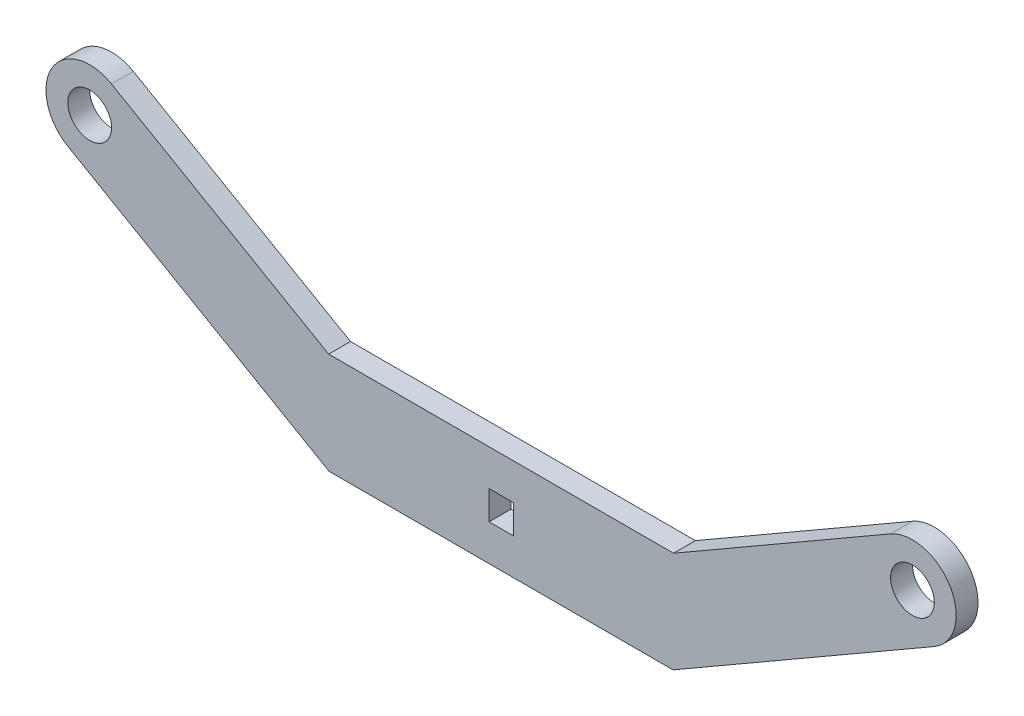
SolidWorks part; units mm, degrees
ref_plane "Front Plane" through (0, 0, 0) normal (0, 0, 1) x (1, 0, 0)
ref_plane "Top Plane" through (0, 0, 0) normal (0, 1, 0) x (1, 0, 0)
ref_plane "Right Plane" through (0, 0, 0) normal (1, 0, 0) x (0, 0, -1)
sketch "Sketch1" plane through (0, 0, 0) normal (0, 0, 1) x (1, 0, 0)
  line L0 (0, 0) -> (238.9657, 0) construction
  line L1 (0, 0) -> (43.9941, -25.4) construction
  line L2 (238.9657, 0) -> (194.9716, -25.4) construction
  line L3 (194.9716, -25.4) -> (43.9941, -25.4) construction
  line L4 (6.35, 10.9985) -> (69.3941, -25.4)
  line L5 (-6.35, -10.9985) -> (69.5301, -54.8079)
  line L6 (119.4829, 0) -> (119.4829, -89.4897) construction
  line L7 (245.3157, -10.9985) -> (169.4356, -54.8079)
  line L8 (232.6157, 10.9985) -> (169.5716, -25.4)
  line L9 (69.3941, -25.4) -> (169.5716, -25.4)
  line L10 (169.4356, -54.8079) -> (69.5301, -54.8079)
  circle A0 centre (0, 0) radius 6.35
  circle A1 centre (238.9657, 0) radius 6.35
  arc A2 (6.35, 10.9985) -> (-6.35, -10.9985) centre (0, 0) ccw
  arc A3 (232.6157, 10.9985) -> (245.3157, -10.9985) centre (238.9657, 0) cw
  dimension "D1" = 238.9657
  dimension "D2" = 12.7
  dimension "D6" = 25.4
  dimension "D3" = 50.8
  dimension "D4" = 30
  dimension "D5" = 30
extrude "Boss-Extrude1" add sketch "Sketch1" along normal blind 6.35
sketch "Sketch2" plane through (0, 0, 6.35) normal (0, 0, 1) x (1, 0, 0)
  line L0 (69.5301, -54.8079) -> (169.5716, -25.4) construction
  line L1 (115.9966, -44.2803) -> (123.1052, -44.2803)
  line L2 (115.9966, -44.2803) -> (115.9966, -35.9277)
  line L3 (115.9966, -35.9277) -> (123.1052, -35.9277)
  line L4 (123.1052, -44.2803) -> (123.1052, -35.9277)
  line L5 (115.9966, -44.2803) -> (123.1052, -35.9277) construction
  line L6 (115.9966, -35.9277) -> (123.1052, -44.2803) construction
  point P4 (119.5509, -40.104)
  point P9 (119.5509, -40.104)
extrude "Cut-Extrude1" cut sketch "Sketch2" against normal up to next
